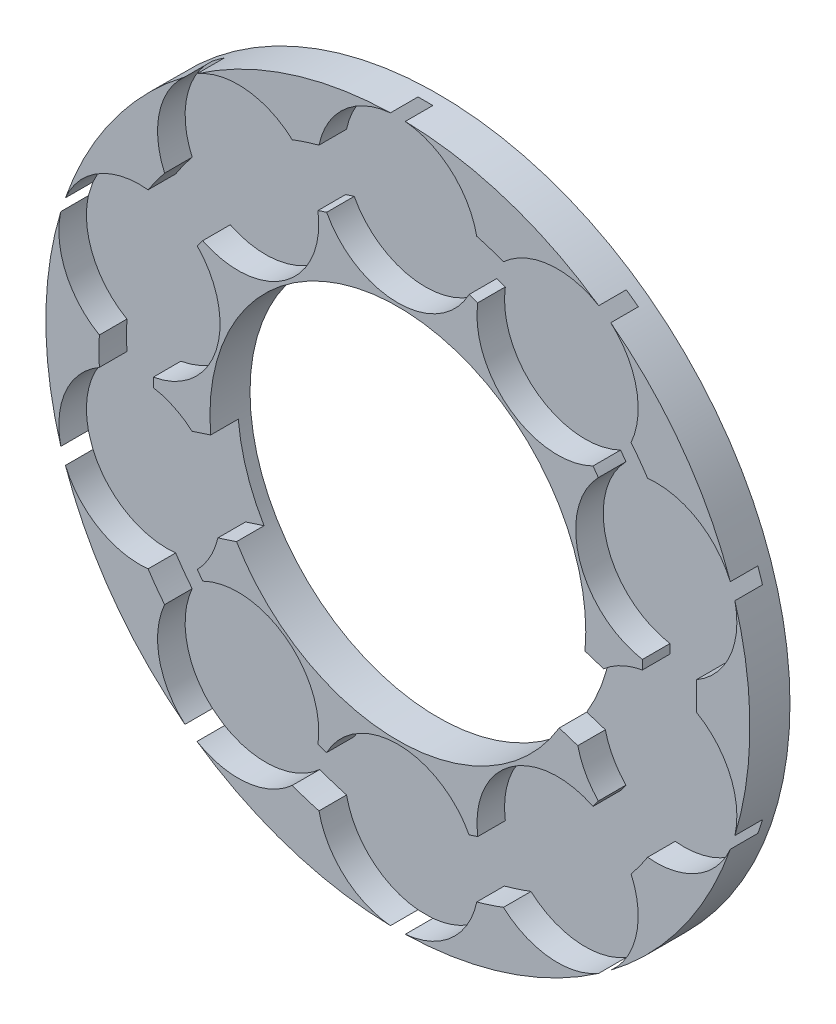
SolidWorks part; units mm, degrees
ref_plane "Front Plane" through (0, 0, 0) normal (0, 0, 1) x (1, 0, 0)
ref_plane "Top Plane" through (0, 0, 0) normal (0, 1, 0) x (1, 0, 0)
ref_plane "Right Plane" through (0, 0, 0) normal (1, 0, 0) x (0, 0, -1)
sketch "Sketch1" plane through (0, 0, 0) normal (0, 0, 1) x (1, 0, 0)
  circle A0 centre (0, 0) radius 42.1482
  circle A1 centre (0, 0) radius 22.5
  dimension "D1" = 45
  dimension "D2" = 84.2965
extrude "Basic Shape" add sketch "Sketch1" along normal blind 4.8
sketch "Sketch2" plane through (0, 0, 4.8) normal (0, 0, 1) x (1, 0, 0)
  line L0 (0, 0) -> (0, -22.5) construction
  line L1 (0, -22.5) -> (0, -42.1482) construction
  circle A0 centre (0, -32.53) radius 9.65
  circle A1 centre (0, 0) radius 22.5 construction
  circle A2 centre (0, 0) radius 42.1482 construction
  dimension "D1" = 19.3
  dimension "D2" = 32.53
extrude "Battery Slot" cut sketch "Sketch2" against normal blind 3.3
pattern_circular "Battery Slot Pattern" count 10 over 360 about axis through (0, 0, 0) along (0, 0, 1) of "Battery Slot"
sketch "Sketch3" plane through (0, 0, 4.8) normal (0, 0, 1) x (1, 0, 0)
  circle A0 centre (0, 0) radius 32.53 construction
  circle A1 centre (0, 0) radius 29.28
  circle A2 centre (0, 0) radius 35.78
  dimension "D1" = 3.25
  dimension "D2" = 3.25
extrude "Bus Slot" cut sketch "Sketch3" against normal blind 3.3
sketch "Sketch4" plane through (0, 0, 4.8) normal (0, 0, 1) x (1, 0, 0)
  line L0 (0, 0) -> (-40.0854, -13.0245) construction
  line L1 (-24.6333, -2.7465) -> (-21.5431, -12.2571) construction
  line L2 (-24.6333, -2.7465) -> (-19.878, -1.2014)
  line L3 (-19.878, -1.2014) -> (-16.7878, -10.712)
  line L4 (-16.7878, -10.712) -> (-21.5431, -12.2571)
  arc A0 (-40.3515, -12.1749) -> (-39.8013, -13.8683) centre (0, 0) ccw construction
  arc A1 (-24.6333, -2.7465) -> (-21.5431, -12.2571) centre (-30.9379, -10.0523) cw
  arc A2 (-24.0052, -16.7651) -> (-29.2749, -0.5467) centre (-30.9379, -10.0523) ccw construction
  point P15 (-21.7602, -7.0703)
  dimension "D1" = 10
  dimension "D2" = 5
extrude "Wire Slit" cut sketch "Sketch4" against normal blind 3.3
mirror "Wire Slit Mirror" about plane through (0, 0, 0) normal (1, 0, 0) of "Wire Slit"
